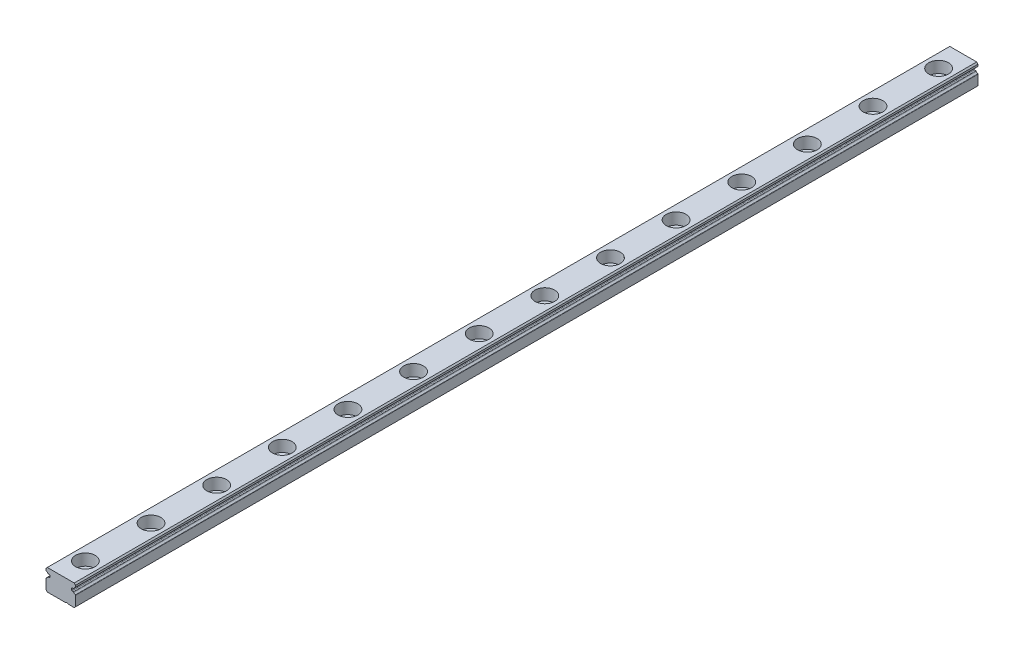
SolidWorks part; units mm, degrees
ref_plane "Front Plane" through (0, 0, 0) normal (0, 0, 1) x (1, 0, 0)
ref_plane "Top Plane" through (0, 0, 0) normal (0, 1, 0) x (1, 0, 0)
ref_plane "Right Plane" through (0, 0, 0) normal (1, 0, 0) x (0, 0, -1)
sketch "Sketch1" plane through (0, 0, 0) normal (0, 0, 1) x (1, 0, 0)
  line L0 (-4.5, 0) -> (4.5, 0) construction
  line L1 (0, -3.25) -> (0, 3.25) construction
  line L2 (0, 3.25) -> (0, -3.25) construction
  line L3 (-3, 3.25) -> (3, 3.25) construction
  line L4 (-1.75, -0.25) -> (1.75, -0.25) construction
  point P0 (0, -0.25)
  point P3 (-4.5, -3.25)
  point P4 (0, 0)
  point P8 (0, 0)
  point P11 (0, 3.25)
  point P15 (0, 3.25)
  point P17 (0, -0.25)
  point P18 (4.5, 3.25)
  point P20 (-4.5, 3.25)
  dimension "Rail Width" = 9
  dimension "Rail Height" = 6.5
  dimension "Mounting Hole Depth" = 3
  dimension "Mounting Hole Counterbore Diameter" = 6
  dimension "Mounting Hole Diameter" = 3.5
sketch "Sketch2" plane through (0, 0, 0) normal (1, 0, 0) x (0, 0, -1)
  line L0 (137.5, 0) -> (-137.5, 0) construction
  line L1 (-7, 3.25) -> (7, 3.25) construction
  line L3 (0, 3.25) -> (0, 0) construction
  point P0 (-130, 0)
  point P4 (0, 0)
  point P5 (-110, 0)
  point P6 (-120, 0)
  point P9 (-130, 3.25)
  point P10 (0, 3.25)
  point P11 (137.5, 3.25)
  point P13 (-137.5, 3.25)
  point P14 (120, 0)
  point P17 (-137.5, -3.25)
  dimension "Rail Length" = 275
  dimension "Mounting Hole Center to Edge" = 7.5
  dimension "Mounting Hole Center to Center" = 20
  dimension "Number of Mounting Holes" = 14
  dimension "Break Line" = 10
sketch "Sketch3" plane through (0, 0, 0) normal (0, 0, 1) x (1, 0, 0)
  point P0 (0, 3.25)
  line B0 (-4.5, 0.1917) -> (-4.5, -2.85)
  line B1 (-4.5, -2.85) -> (-4.1, -3.25)
  line B2 (-4.1, -3.25) -> (1.4, -3.25)
  line B3 (2.2, -3.25) -> (4.1, -3.25)
  line B4 (4.1, -3.25) -> (4.5, -2.85)
  line B5 (4.5, -2.85) -> (4.5, 0.1917)
  line B6 (3.8235, 0.8135) -> (3.4826, 0.8434)
  line B7 (3.3, 1.0426) -> (3.3, 1.4574)
  line B8 (3.4826, 1.6566) -> (3.8235, 1.6865)
  line B9 (4.5, 2.3083) -> (4.5, 2.85)
  line B10 (4.5, 2.85) -> (4.1, 3.25)
  line B11 (4.1, 3.25) -> (-4.1, 3.25)
  line B12 (-4.1, 3.25) -> (-4.5, 2.85)
  line B13 (-4.5, 2.85) -> (-4.5, 2.3083)
  line B14 (-3.8235, 1.6865) -> (-3.4826, 1.6566)
  line B15 (-3.3, 1.4574) -> (-3.3, 1.0426)
  line B16 (-3.4826, 0.8434) -> (-3.8235, 0.8135)
  arc B17 (2.2, -3.25) -> (1.4, -3.25) centre (1.8, -3.55) ccw
  arc B18 (4.5, 0.1917) -> (4.4087, 0.3297) centre (4.35, 0.1917) ccw
  arc B19 (3.9395, 0.7405) -> (4.4087, 0.3297) centre (4.8, 1.25) ccw
  arc B20 (3.9395, 0.7405) -> (3.8235, 0.8135) centre (3.8104, 0.6641) ccw
  arc B21 (3.3, 1.0426) -> (3.4826, 0.8434) centre (3.5, 1.0426) ccw
  arc B22 (3.4826, 1.6566) -> (3.3, 1.4574) centre (3.5, 1.4574) ccw
  arc B23 (3.8235, 1.6865) -> (3.9395, 1.7595) centre (3.8104, 1.8359) ccw
  arc B24 (4.4087, 2.1703) -> (3.9395, 1.7595) centre (4.8, 1.25) ccw
  arc B25 (4.4087, 2.1703) -> (4.5, 2.3083) centre (4.35, 2.3083) ccw
  arc B26 (-4.5, 2.3083) -> (-4.4087, 2.1703) centre (-4.35, 2.3083) ccw
  arc B27 (-3.9395, 1.7595) -> (-4.4087, 2.1703) centre (-4.8, 1.25) ccw
  arc B28 (-3.9395, 1.7595) -> (-3.8235, 1.6865) centre (-3.8104, 1.8359) ccw
  arc B29 (-3.3, 1.4574) -> (-3.4826, 1.6566) centre (-3.5, 1.4574) ccw
  arc B30 (-3.4826, 0.8434) -> (-3.3, 1.0426) centre (-3.5, 1.0426) ccw
  arc B31 (-3.8235, 0.8135) -> (-3.9395, 0.7405) centre (-3.8104, 0.6641) ccw
  arc B32 (-4.4087, 0.3297) -> (-3.9395, 0.7405) centre (-4.8, 1.25) ccw
  arc B33 (-4.4087, 0.3297) -> (-4.5, 0.1917) centre (-4.35, 0.1917) ccw
sketch_block_instance "9mm Block-1"
sketch_block "9mm Block"
extrude "Boss-Extrude1" add sketch "Sketch3" against normal up to vertex (137.5 mm away) from vertex at 137.5 starting at point (0, 0, 137.5)
ref_plane "Plane1" through (0, 0, 130) normal (0, 0, 1) x (1, 0, 0)
sketch "Sketch4" plane through (0, 0, 130) normal (0, 0, 1) x (1, 0, 0)
  line L0 (0, 3.25) -> (0, -3.25)
  line L1 (0, -3.25) -> (-1.75, -3.25)
  line L3 (-1.75, -3.25) -> (-1.75, -0.25)
  line L4 (-1.75, -0.25) -> (-3, -0.25)
  line L5 (-3, -0.25) -> (-3, 3.25)
  line L6 (-3, 3.25) -> (0, 3.25)
revolve "Cut-Revolve1" cut sketch "Sketch4" angle 360 about L0
sketch "Sketch6" plane through (0, 0, 0) normal (1, 0, 0) x (0, 0, -1)
  line L0 (-127, -0.25) -> (-133, -0.25) construction
  line L5 (-127, -0.25) -> (-133, -0.25)
  line L17 (-131.75, -0.25) -> (-131.75, -3.25) construction
  line L18 (-128.25, -3.25) -> (-128.25, -0.25) construction
  line L32 (-127, -0.25) -> (-127, 3.25) construction
  line L33 (-133, 3.25) -> (-133, -0.25) construction
  line L34 (-131.75, -0.25) -> (-131.75, -3.25)
  line L35 (-128.25, -3.25) -> (-128.25, -0.25)
  line L36 (-127, -0.25) -> (-127, 3.25)
  line L37 (-133, 3.25) -> (-133, -0.25)
  line L38 (0, 3.25) -> (0, -3.25) construction
  line L40 (133, 3.25) -> (133, -0.25)
  line L41 (127, -0.25) -> (127, 3.25)
  line L42 (128.25, -3.25) -> (128.25, -0.25)
  line L43 (131.75, -0.25) -> (131.75, -3.25)
  line L44 (127, -0.25) -> (133, -0.25)
sketch "Sketch7" plane through (0, 0, 0) normal (0, 0, 1) x (1, 0, 0)
  line L0 (3, -0.25) -> (3, 3.25) construction
  line L1 (-3, 3.25) -> (-3, -0.25) construction
  line L2 (3, -0.25) -> (3, 3.25)
  line L3 (-3, 3.25) -> (-3, -0.25)
  line L4 (1.75, -3.0525) -> (1.75, -0.25) construction
  line L11 (1.75, -3.0525) -> (1.75, -0.25)
  line L18 (-1.75, -0.25) -> (-1.75, -3.25) construction
  line L32 (3, -0.25) -> (-3, -0.25) construction
  line L34 (-1.75, -0.25) -> (-1.75, -3.25)
  line L37 (3, -0.25) -> (-3, -0.25)
pattern_linear "LPattern1" count 14 spacing 20 along (0, 0, -1) of "Cut-Revolve1"
equation "\"D3@LPattern1\"=\"Mounting Hole Center to Center@Sketch2\""
equation "\"D1@LPattern1\"=\"Number of Mounting Holes@Sketch2\""
equation "\"Break Line@Sketch2\"=\"Mounting Hole Center to Center@Sketch2\"/2"
